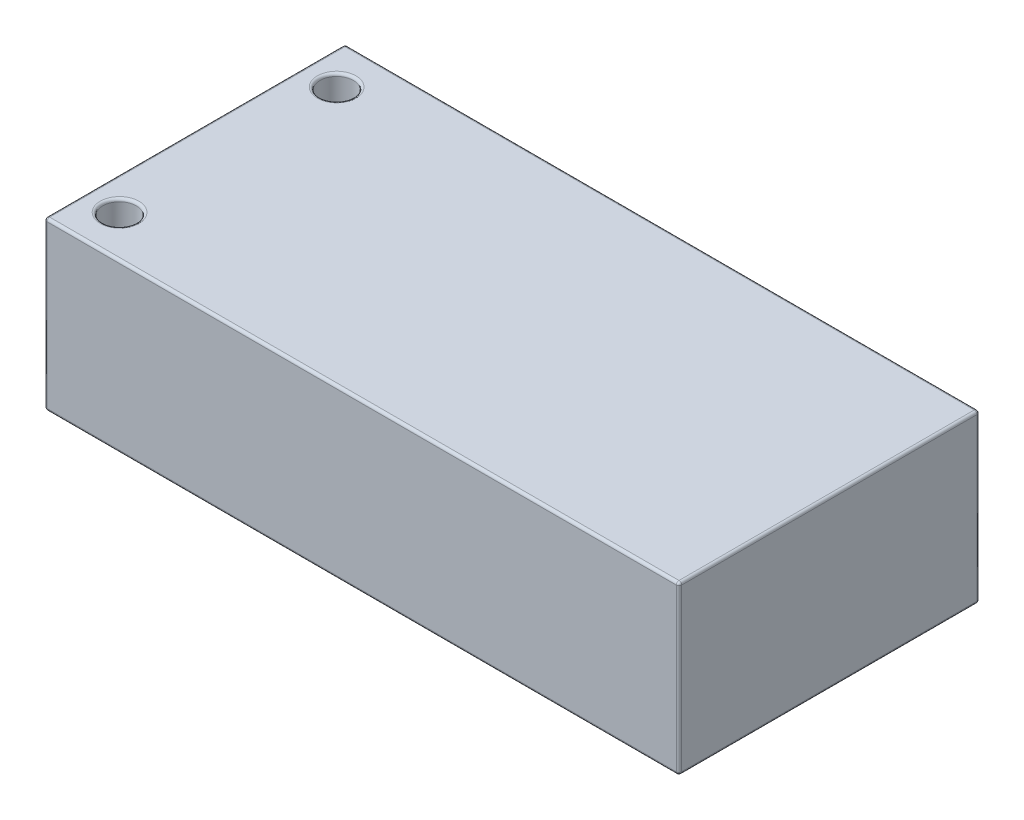
SolidWorks part; units mm, degrees
ref_plane "Front Plane" through (0, 0, 0) normal (0, 0, 1) x (1, 0, 0)
ref_plane "Top Plane" through (0, 0, 0) normal (0, 1, 0) x (1, 0, 0)
ref_plane "Right Plane" through (0, 0, 0) normal (1, 0, 0) x (0, 0, -1)
sketch "Sketch1" plane through (0, 0, 0) normal (0, 1, 0) x (1, 0, 0)
  line L1 (0, 0) -> (95, 0)
  line L2 (0, 0) -> (0, 45)
  line L3 (0, 45) -> (95, 45)
  line L4 (95, 0) -> (95, 45)
  dimension "D1" = 45
  dimension "D2" = 95
extrude "Boss-Extrude1" add sketch "Sketch1" along normal blind 25
sketch "Sketch2" plane through (0, 25, 0) normal (0, 1, 0) x (1, 0, 0)
  line L0 (0, 45) -> (0, 0) construction
  line L1 (95, 45) -> (0, 45) construction
  line L2 (0, 0) -> (95, 0) construction
  circle A0 centre (5, 38.75) radius 2.5
  circle A1 centre (5, 6.25) radius 2.5
  point P8 (0, 0)
  dimension "D1" = 5
  dimension "D2" = 5
  dimension "D3" = 6.25
  dimension "D4" = 6.25
extrude "Cut-Extrude1" cut sketch "Sketch2" against normal blind 10
fillet "Fillet1" radius 0.4 14 edges at (95, 12.5, -45) (95, 0, -22.5) (47.5, 0, -45) (0, 12.5, -45) (0, 0, -22.5) (0, 12.5, 0) (95, 12.5, 0) (47.5, 0, 0) (47.5, 25, -45) (95, 25, -22.5) (47.5, 25, 0) (0, 25, -22.5) (5, 25, -3.75) (5, 25, -36.25)
